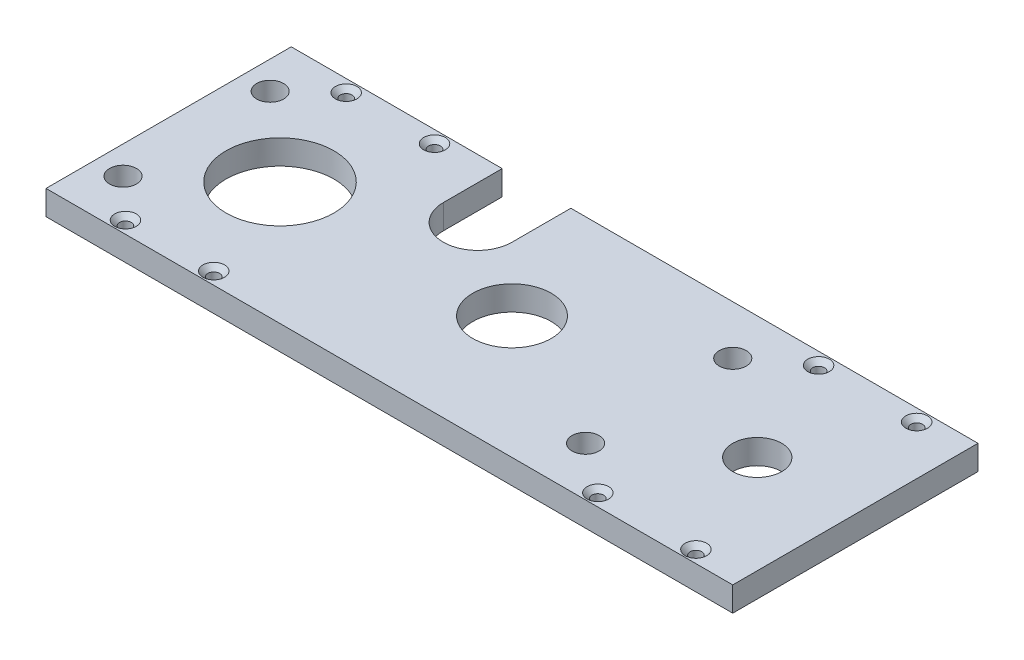
SolidWorks part; units mm, degrees
ref_plane "Front Plane" through (0, 0, 0) normal (0, 0, 1) x (1, 0, 0)
ref_plane "Top Plane" through (0, 0, 0) normal (0, 1, 0) x (1, 0, 0)
ref_plane "Right Plane" through (0, 0, 0) normal (1, 0, 0) x (0, 0, -1)
sketch "Sketch1" plane through (0, 0, 0) normal (0, 1, 0) x (1, 0, 0)
  line L0 (36.4981, 0) -> (1.5047, 0) construction
  line L3 (36.4981, -25) -> (36.4981, 25)
  line L8 (36.4981, -25) -> (-103.5019, -25)
  line L9 (-103.5019, 25) -> (36.4981, 25)
  line L12 (-103.5019, -25) -> (-103.5019, 25)
  circle A3 centre (16.4981, 0) radius 5
  point P12 (-14.0919, 0)
  dimension "D1" = 140
  dimension "D2" = 50
  dimension "D5" = 10
  dimension "D3" = 20
  dimension "D4" = 36.4981
extrude "Boss-Extrude2" add sketch "Sketch1" along normal blind 5
sketch "Sketch5" plane through (0, 0, 0) normal (0, -1, 0) x (1, 0, 0)
  circle A1 centre (-33.5019, 0) radius 8
  circle A2 centre (16.4981, 0) radius 5 construction
  point P4 (-33.5019, 0)
  dimension "D1" = 16
  dimension "D2" = 50
extrude "Cut-Extrude1" cut sketch "Sketch5" against normal up to next
sketch "Sketch14" plane through (0, 5, 0) normal (0, 1, 0) x (1, 0, 0)
  line L0 (-33.5019, 8) -> (-33.5019, -8) construction
  line L1 (-33.5019, 0) -> (-67.0576, 0) construction
  circle A0 centre (-33.5019, 0) radius 8 construction
  circle A1 centre (-80.8019, 0) radius 11
  dimension "D1" = 47.3
extrude "Cut-Extrude2" cut sketch "Sketch14" against normal up to next
sketch "Sketch15" plane through (0, 5, 0) normal (0, 1, 0) x (1, 0, 0)
  line L0 (-70.4012, 25) -> (-40.5699, 25) construction
  line L1 (36.4981, 25) -> (-103.5019, 25) construction
  line L2 (-80.8019, 0) -> (-80.8019, 23.6981) construction
  line L3 (-70.4012, 22.5) -> (-40.5699, 22.5) construction
  line L4 (16.4981, 5) -> (16.4981, -5) construction
  line L5 (11.4981, 0) -> (21.4981, 0) construction
  line L6 (-59.4648, 0) -> (-51.6098, 0) construction
  line L7 (-33.5019, 0) -> (-67.0576, 0) construction
  line L8 (36.4981, 22.5) -> (-7.4815, 22.5) construction
  line L9 (36.4981, -25) -> (36.4981, 25) construction
  line L10 (36.4981, -22.5) -> (-5.445, -22.5) construction
  circle A0 centre (16.4981, 0) radius 5 construction
  point P9 (-71.8019, 22.5)
  point P13 (-89.8019, 22.5)
  point P15 (-71.8019, -22.5)
  point P16 (-89.8019, -22.5)
  point P30 (26.4981, 22.5)
  point P31 (6.4981, 22.5)
  point P32 (26.4981, -22.5)
  point P33 (6.4981, -22.5)
  dimension "D1" = 2.5
  dimension "D2" = 9
  dimension "D3" = 45
  dimension "D4" = 10
hole_wizard "CSK for M2 Countersunk Flat Head Screw1" positions "Sketch16" profile "Sketch17" countersink size "M2" standard "ISO" end condition up to next
sketch "Sketch16" plane through (0, 5, 0) normal (0, 1, 0) x (1, 0, 0)
  point P0 (-89.8019, 22.5)
  point P3 (-71.8019, 22.5)
  point P6 (-71.8019, -22.5)
  point P9 (-89.8019, -22.5)
  point P12 (6.4981, 22.5)
  point P15 (26.4981, 22.5)
  point P18 (6.4981, -22.5)
  point P21 (26.4981, -22.5)
sketch "Sketch17" plane through (-89.8019, 5, -22.5) normal (1, 0, 0) x (0, 0, 1)
  line L0 (0, 0) -> (0, 5)
  line L1 (0, 5) -> (1.2, 5)
  line L2 (1.2, 5) -> (1.2, 1)
  line L3 (1.2, 1) -> (2.2, 0)
  line L5 (2.2, 0) -> (0, 0)
  line L6 (-1.2, 1) -> (-2.2, 0) construction
  line L11 (0, -6.35) -> (0, 107.95) construction
  dimension "Thru Hole Dia." = 2.4
  dimension "Thru Hole Depth" = 5
  dimension "Near C'Sink Dia." = 4.4
  dimension "Near C'Sink Angle" = 90
hole_wizard "M5 Clearance Hole1" positions "Sketch18" profile "Sketch19" hole size "M5" standard "ISO"
sketch "Sketch18" plane through (0, 0, 0) normal (0, -1, 0) x (-1, 0, 0)
  line L6 (3.5019, -25) -> (3.5019, 25) construction
  line L7 (103.5019, -25) -> (-36.4981, -25) construction
  line L8 (-36.4981, 25) -> (103.5019, 25) construction
  line L10 (9.2785, 0) -> (-4.0934, 0) construction
  circle A3 centre (-16.4981, 0) radius 5 construction
  circle A7 centre (80.8019, 0) radius 11 construction
  point P24 (97.8019, 15)
  point P26 (97.8019, -15)
  point P56 (3.5019, -15)
  point P62 (3.5019, 15)
  dimension "D1" = 20
  dimension "D2" = 15
  dimension "D3" = 17
  dimension "D4" = 17
sketch "Sketch19" plane through (-97.8019, 0, -15) normal (1, 0, 0) x (0, 0, -1)
  line L0 (0, 0) -> (0, 21.4024)
  line L1 (0, 21.4024) -> (2.75, 19.75)
  line L2 (2.75, 19.75) -> (2.75, 0)
  line L5 (2.75, 0) -> (0, 0)
  line L10 (0, 21.4024) -> (-2.75, 19.75) construction
  line L11 (0, -6.35) -> (0, 107.95) construction
  dimension "Hole Dia." = 5.5
  dimension "Hole Depth" = 19.75
  dimension "Drill Angle" = 118
sketch "Sketch20" plane through (0, 0, 0) normal (0, -1, 0) x (-1, 0, 0)
  line L0 (53.5019, 14.5) -> (53.5019, 25) construction
  line L1 (53.5019, 13) -> (25.3019, 13) construction
  line L2 (53.5019, 13) -> (53.5019, 25) construction
  line L3 (46.5019, 13) -> (46.5019, 25)
  line L4 (60.5019, 13) -> (60.5019, 25)
  line L5 (-36.4981, 25) -> (103.5019, 25) construction
  circle A3 centre (-16.4981, 0) radius 5 construction
  arc A5 (46.5019, 13) -> (60.5019, 13) centre (53.5019, 13) ccw
  arc A6 (60.5019, 25) -> (46.5019, 25) centre (53.5019, 25) ccw
  point P8 (53.5019, 19)
  dimension "D1" = 70
  dimension "D3" = 7
  dimension "D2" = 13
extrude "Cut-Extrude3" cut sketch "Sketch20" against normal through all
